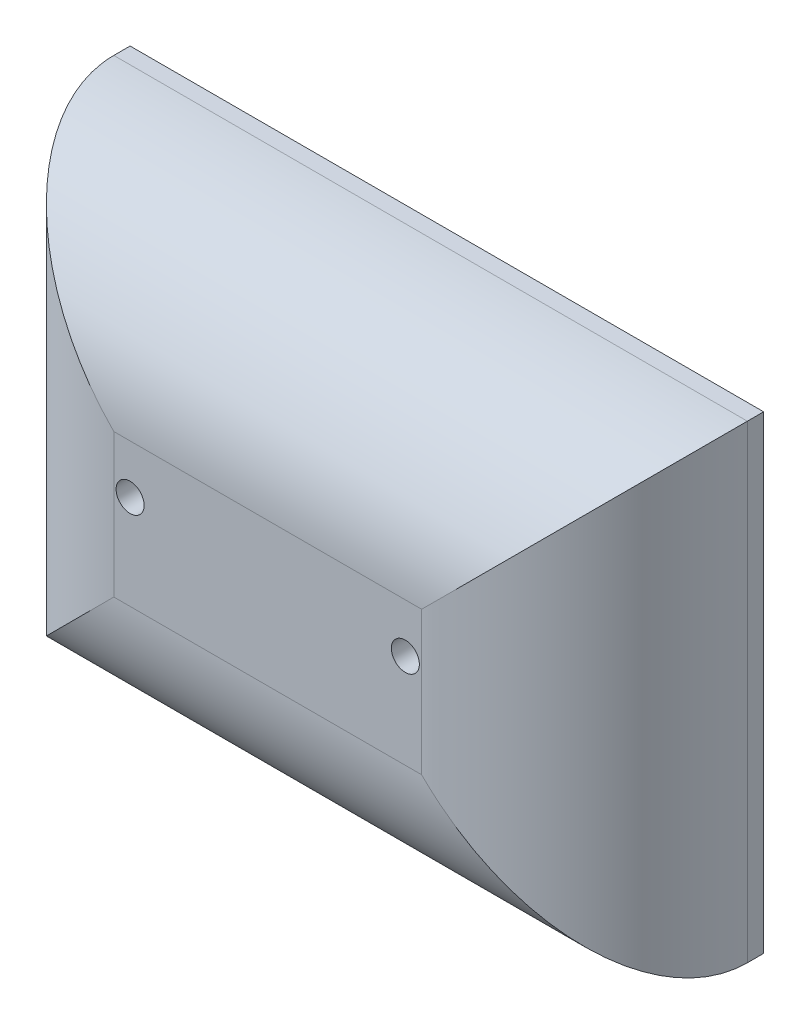
SolidWorks part; units mm, degrees
ref_plane "Ebene vorne" through (0, 0, 0) normal (0, 0, 1) x (1, 0, 0)
ref_plane "Ebene oben" through (0, 0, 0) normal (0, 1, 0) x (1, 0, 0)
ref_plane "Ebene rechts" through (0, 0, 0) normal (1, 0, 0) x (0, 0, -1)
sketch "Skizze2" plane through (0, 0, 0) normal (0, 0, 1) x (1, 0, 0)
  line L1 (97.25, -72) -> (-97.25, -72)
  line L2 (97.25, -72) -> (97.25, 72)
  line L3 (97.25, 72) -> (-97.25, 72)
  line L4 (-97.25, -72) -> (-97.25, 72)
  line L5 (97.25, -72) -> (-97.25, 72) construction
  line L6 (97.25, 72) -> (-97.25, -72) construction
  point P0 (0, 0)
  dimension "D1" = 144
  dimension "D2" = 194.5
extrude "Aufsatz-Linear austragen1" add sketch "Skizze2" along normal blind 55
ref_plane "Ebene1" through (0, 0, 0) normal (0, 1, 0) x (1, 0, 0)
ref_plane "Ebene2" through (0, 0, 0) normal (1, 0, 0) x (0, -1, 0)
sketch "Skizze3" plane through (0, -72, 0) normal (0, -1, 0) x (1, 0, 0)
  line L0 (-97.25, 55) -> (97.25, 55) construction
  line L1 (-97.25, 55) -> (-97.25, 0) construction
  line L2 (-47.25, 55) -> (-31.1876, 55)
  line L3 (-31.1876, 55) -> (-49.0652, 93.4939)
  line L4 (-49.0652, 93.4939) -> (-152.6979, 34.4047)
  line L5 (-152.6979, 34.4047) -> (-97.25, -29.0921)
  line L6 (-97.25, -29.0921) -> (-97.25, 5)
  arc A0 (-47.25, 55) -> (-97.25, 5) centre (-47.25, 5) ccw
  dimension "D1" = 100
extrude "Schnitt-Linear austragen1" cut sketch "Skizze3" against normal through all contours L4 L5 L6 A0 L2 L3
mirror "Spiegeln3" about plane through (0, 0, 0) normal (1, 0, 0) of "Schnitt-Linear austragen1"
sketch "Skizze6" plane through (97.25, 0, 0) normal (1, 0, 0) x (0, 0, -1)
  line L0 (-5, 72) -> (11.0624, 72)
  line L1 (11.0624, 72) -> (-41.4687, 93.5258)
  line L2 (-41.4687, 93.5258) -> (-130.245, 42.9074)
  line L3 (-130.245, 42.9074) -> (-55, -43.2602)
  line L4 (-55, -43.2602) -> (-55, 22)
  line L5 (-55, 72) -> (-55, -72) construction
  line L6 (-5, 72) -> (-55, 72) construction
  arc A0 (-5, 72) -> (-55, 22) centre (-5, 22) ccw
  dimension "D1" = 100
extrude "Schnitt-Linear austragen2" cut sketch "Skizze6" against normal through all
mirror "Spiegeln4" about plane through (0, 0, 0) normal (0, 1, 0) of "Schnitt-Linear austragen2"
sketch "Skizze7" plane through (0, 0, 55) normal (0, 0, 1) x (1, 0, 0)
  line L0 (-97.25, 72) -> (-97.25, -72) construction
  line L1 (-97.25, 72) -> (97.25, 72) construction
  circle A0 centre (-42.25, 7) radius 25.5675
  point P6 (-44.3511, 65.0268)
  dimension "D1" = 55
  dimension "D2" = 65
hole_wizard "Stirnsenkung für M4 Senkschraube (Kopf Button)1" positions "Skizze10" profile "Skizze8" counterbore size "M4" standard "ANSI Metrisch" end condition through all
sketch "Skizze10" plane through (0, 0, 55) normal (0, 0, 1) x (1, 0, 0)
  point P0 (-42.25, 7)
sketch "Skizze8" plane through (-42.25, 7, 55) normal (1, 0, 0) x (0, -1, 0)
  line L0 (0, 0) -> (0, 55)
  line L1 (0, 55) -> (2.25, 55)
  line L3 (2.25, 55) -> (2.25, 50)
  line L4 (2.25, 50) -> (4.3, 50)
  line L5 (4.3, 50) -> (4.3, 0)
  line L7 (4.3, 0) -> (0, 0)
  line L11 (0, -6.35) -> (0, 107.95) construction
  dimension "Bohrerdurchmesser" = 4.5
  dimension "Bohrungstiefe" = 55
  dimension "Senkdurchmesser2" = 8.6
  dimension "Senktiefe2" = 50
mirror "Spiegeln5" about plane through (0, 0, 0) normal (1, 0, 0) of "Stirnsenkung für M4 Senkschraube (Kopf Button)1"
